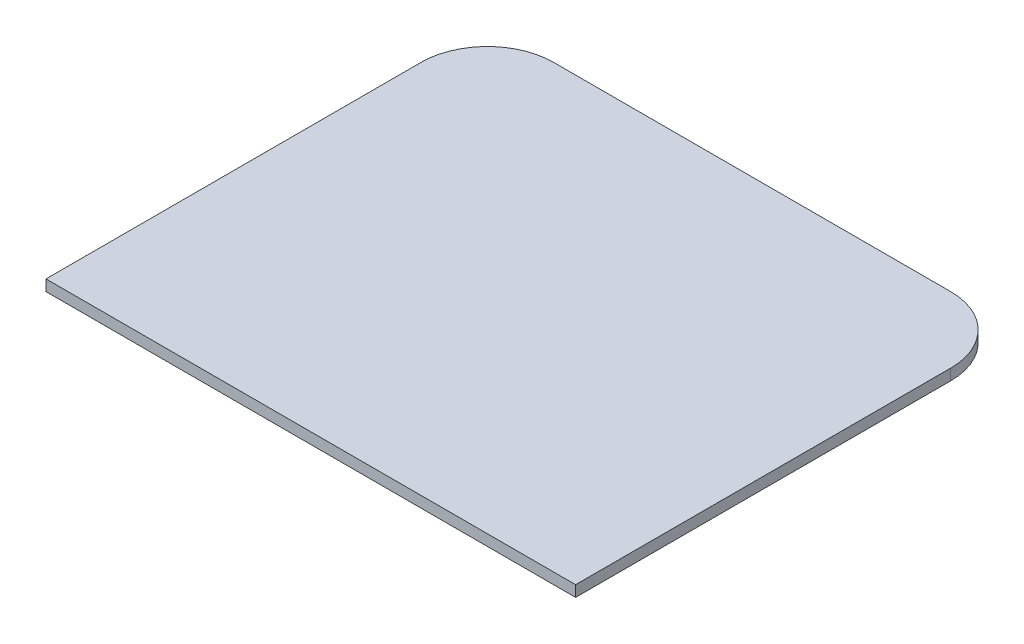
SolidWorks part; units mm, degrees
ref_plane "Front Plane" through (0, 0, 0) normal (0, 0, 1) x (1, 0, 0)
ref_plane "Top Plane" through (0, 0, 0) normal (0, 1, 0) x (1, 0, 0)
ref_plane "Right Plane" through (0, 0, 0) normal (1, 0, 0) x (0, 0, -1)
sketch "Sketch1" plane through (0, 0, 0) normal (0, 1, 0) x (1, 0, 0)
  line L1 (94.85, -65.9167) -> (-57.55, -65.9167)
  line L2 (94.85, -65.9167) -> (94.85, 61.0833)
  line L3 (94.85, 61.0833) -> (-57.55, 61.0833)
  line L4 (-57.55, -65.9167) -> (-57.55, 61.0833)
  dimension "D1" = 152.4
  dimension "D2" = 127
extrude "Boss-Extrude1" add sketch "Sketch1" along normal blind 3.175
fillet "Fillet1" radius 19.05 1 edges at (-57.55, 1.5875, -61.0833)
fillet "Fillet2" radius 19.05 1 edges at (94.85, 1.5875, -61.0833)
